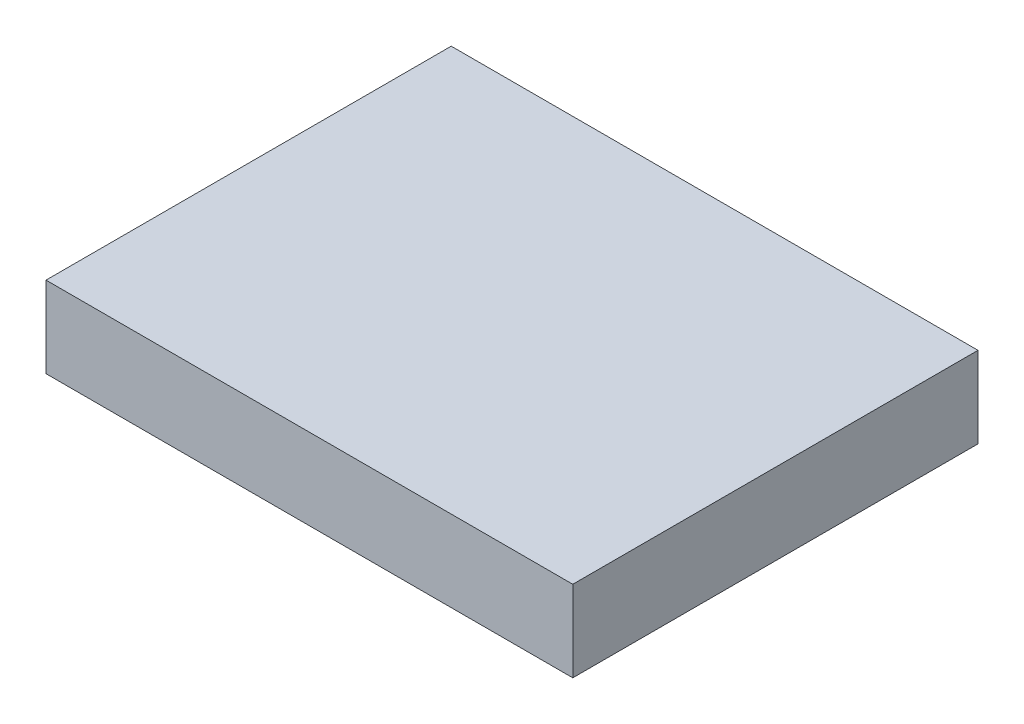
SolidWorks part; units mm, degrees
ref_plane "Front Plane" through (0, 0, 0) normal (0, 0, 1) x (1, 0, 0)
ref_plane "Top Plane" through (0, 0, 0) normal (0, 1, 0) x (1, 0, 0)
ref_plane "Right Plane" through (0, 0, 0) normal (1, 0, 0) x (0, 0, -1)
sketch "Sketch1" plane through (0, 0, 0) normal (0, 1, 0) x (1, 0, 0)
  line L0 (0, 0) -> (330.2, 0)
  line L1 (330.2, 0) -> (330.2, 203.2)
  line L2 (0, 0) -> (0, 203.2)
  line L3 (165.1, 0) -> (165.1, 254)
  line L4 (0, 203.2) -> (0, 254)
  line L5 (0, 254) -> (330.2, 254)
  line L6 (330.2, 254) -> (330.2, 203.2)
  arc A0 (0, 203.2) -> (165.1, 254) centre (158.3572, -17.7734) cw construction
  arc A1 (330.2, 203.2) -> (165.1, 254) centre (169.8499, -24.2503) ccw construction
  point P8 (165.1, 0)
  dimension "D1" = 330.2
  dimension "D2" = 203.2
  dimension "D3" = 254
extrude "Boss-Extrude1" add sketch "Sketch1" along normal blind 50.8 contours L5 L4 L2 L0 L3 | L6 L5 L3 L0 L1
